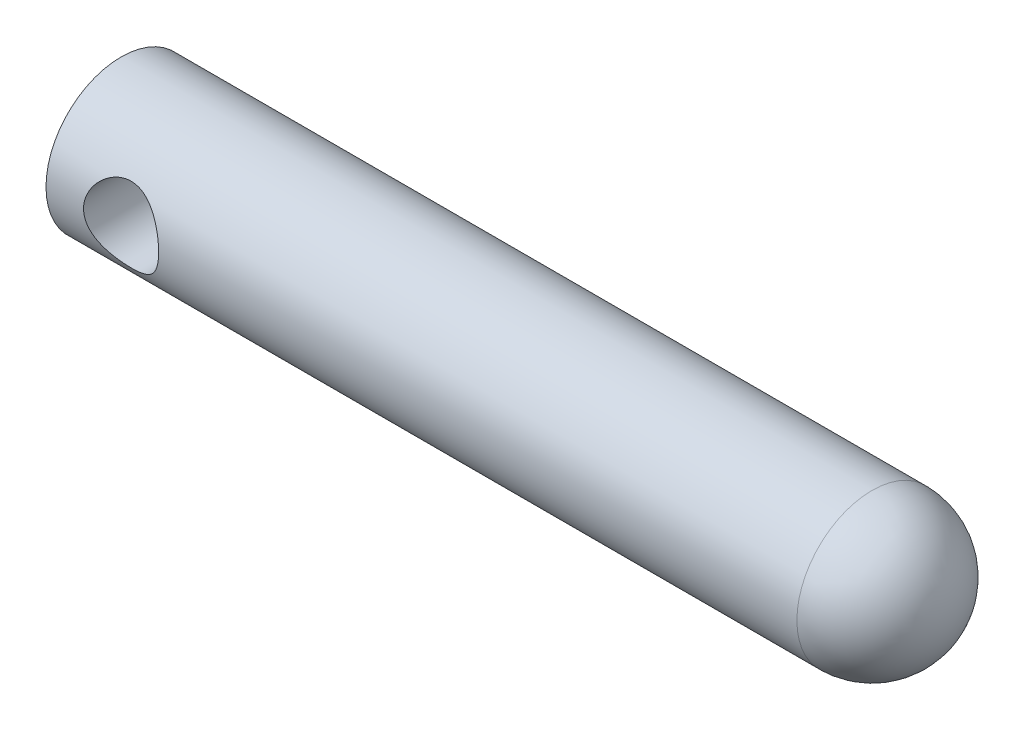
SolidWorks part; units mm, degrees
ref_plane "Front Plane" through (0, 0, 0) normal (0, 0, 1) x (1, 0, 0)
ref_plane "Top Plane" through (0, 0, 0) normal (0, 1, 0) x (1, 0, 0)
ref_plane "Right Plane" through (0, 0, 0) normal (1, 0, 0) x (0, 0, -1)
sketch "Sketch1" plane through (0, 0, 0) normal (1, 0, 0) x (0, 0, -1)
  circle A0 centre (0, 0) radius 2
extrude "Boss-Extrude1" add sketch "Sketch1" along normal blind 22 contours A0
ref_plane "Plane1" through (0, 0, 2) normal (0, 0, 1) x (1, 0, 0)
sketch "Sketch2" plane through (0, 0, 2) normal (0, 0, 1) x (1, 0, 0)
  circle A0 centre (2, 0) radius 1
extrude "Cut-Extrude1" cut sketch "Sketch2" against normal blind 4
fillet "Fillet2" radius 2 1 edges at (22, 0, -2)
